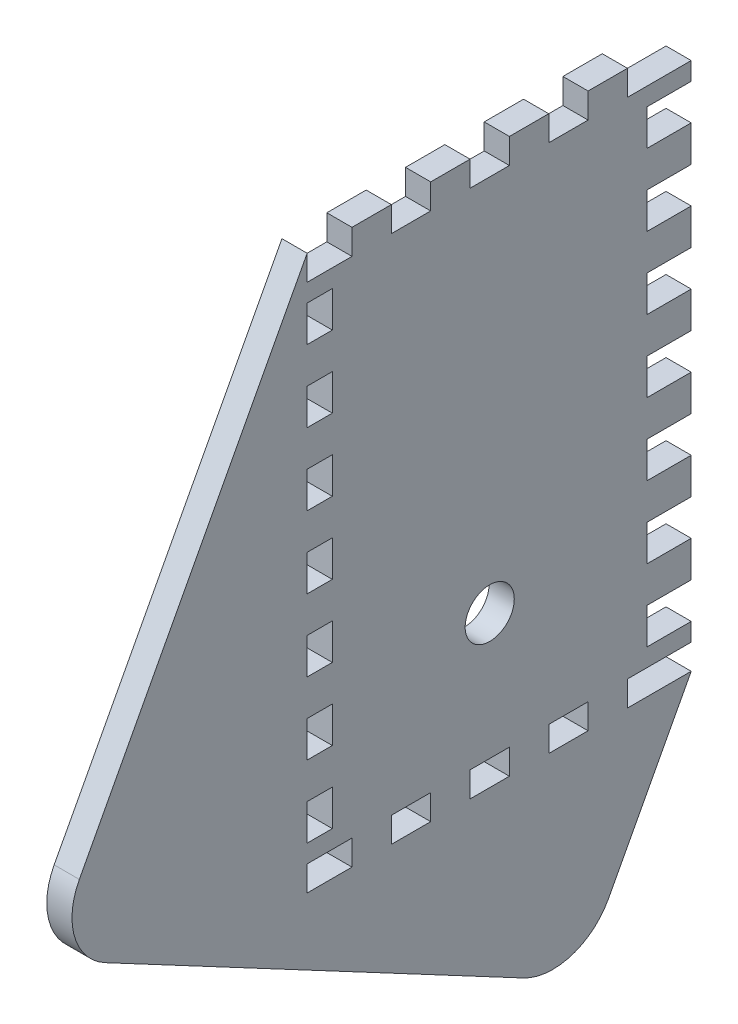
SolidWorks part; units mm, degrees
ref_plane "Piano frontale" through (0, 0, 0) normal (0, 0, 1) x (1, 0, 0)
ref_plane "Piano superiore" through (0, 0, 0) normal (0, 1, 0) x (1, 0, 0)
ref_plane "Piano destro" through (0, 0, 0) normal (1, 0, 0) x (0, 0, -1)
sketch "Schizzo1" plane through (0, 0, 0) normal (1, 0, 0) x (0, 0, -1)
  line L1 (0, 0) -> (50, 0)
  line L2 (0, 0) -> (0, 80)
  line L3 (0, 80) -> (50, 80)
  line L4 (50, 0) -> (50, 80)
  dimension "D1" = 80
  dimension "D2" = 50
extrude "Estrusione-Estrusione1" add sketch "Schizzo1" along normal blind 4
sketch "Schizzo2" plane through (4, 0, 0) normal (1, 0, 0) x (0, 0, -1)
  line L0 (0, 80) -> (0, 0) construction
  line L1 (0, 77.1429) -> (-4, 77.1429)
  line L2 (0, 77.1429) -> (0, 80)
  line L3 (0, 80) -> (-4, 80)
  line L4 (-4, 77.1429) -> (-4, 80)
  line L6 (50, 80) -> (57, 80)
  line L7 (50, 80) -> (50, 77.1429)
  line L8 (50, 77.1429) -> (57, 77.1429)
  line L9 (57, 80) -> (57, 77.1429)
  line L10 (50, 0) -> (57, 0)
  line L11 (50, 0) -> (50, 2.8571)
  line L12 (50, 2.8571) -> (57, 2.8571)
  line L13 (57, 0) -> (57, 2.8571)
  line L14 (0, 0) -> (-4, 0)
  line L15 (0, 0) -> (0, 2.8571)
  line L16 (0, 2.8571) -> (-4, 2.8571)
  line L17 (-4, 0) -> (-4, 2.8571)
  dimension "D1" = 4
  dimension "D2" = 7
  dimension "D3" = 2.8571
  dimension "D4" = 2.8571
extrude "Estrusione-Estrusione2" add sketch "Schizzo2" against normal blind 4
sketch "Schizzo3" plane through (4, 0, 0) normal (1, 0, 0) x (0, 0, -1)
  line L0 (0, 77.1429) -> (0, 2.8571) construction
  line L1 (0, 71.4286) -> (-4, 71.4286)
  line L2 (0, 71.4286) -> (0, 65.7143)
  line L3 (0, 65.7143) -> (-4, 65.7143)
  line L4 (-4, 71.4286) -> (-4, 65.7143)
  line L5 (50, 2.8571) -> (50, 77.1429) construction
  line L6 (50, 71.4286) -> (57, 71.4286)
  line L7 (50, 71.4286) -> (50, 65.7143)
  line L8 (50, 65.7143) -> (57, 65.7143)
  line L9 (57, 71.4286) -> (57, 65.7143)
  line L10 (-4, 77.1429) -> (0, 77.1429) construction
  line L11 (-4, 80) -> (-4, 77.1429) construction
  line L12 (57, 77.1429) -> (57, 80) construction
  dimension "D1" = 5.7143
  dimension "D2" = 5.7143
extrude "Estrusione-Estrusione3" add sketch "Schizzo3" against normal blind 4
pattern_linear "Ripetizione a L1" count 6 spacing 11.4286 along (0, -1, 0) of "Estrusione-Estrusione3"
sketch "Schizzo4" plane through (4, 0, 0) normal (1, 0, 0) x (0, 0, -1)
  line L0 (57, 80) -> (-4, 80) construction
  line L1 (3.125, 80) -> (9.375, 80)
  line L2 (3.125, 80) -> (3.125, 84)
  line L3 (3.125, 84) -> (9.375, 84)
  line L4 (9.375, 80) -> (9.375, 84)
  line L5 (-4, 0) -> (57, 0) construction
  line L6 (3.125, 0) -> (9.375, 0)
  line L7 (3.125, 0) -> (3.125, -4)
  line L8 (3.125, -4) -> (9.375, -4)
  line L9 (9.375, 0) -> (9.375, -4)
  line L10 (0, 77.1429) -> (0, 71.4286) construction
  point P14 (6.25, 0)
  dimension "D1" = 3.125
  dimension "D2" = 6.25
  dimension "D3" = 4
  dimension "D4" = 4
extrude "Estrusione-Estrusione4" add sketch "Schizzo4" against normal blind 4
pattern_linear "Ripetizione a L2" count 4 spacing 12.5 along (0, 0, -1) of "Estrusione-Estrusione4"
sketch "Schizzo5" plane through (4, 0, 0) normal (1, 0, 0) x (0, 0, -1)
  line L0 (46.875, -4) -> (57, -4)
  line L1 (57, -4) -> (39.1601, -37.552)
  line L2 (39.1601, -37.552) -> (-44.873, 7.1291)
  line L3 (-44.873, 7.1291) -> (-4, 84)
  line L4 (-4, 84) -> (-4, 80)
  line L5 (-4, 80) -> (-4, 77.1429) construction
  line L6 (3.125, 80) -> (-4, 80) construction
  line L7 (-4, 80) -> (-4, -4)
  line L8 (-4, -4) -> (46.875, -4)
  dimension "D1" = 4
  dimension "D2" = 10.125
  dimension "D3" = 62
  dimension "D4" = 38
extrude "Estrusione-Estrusione5" add sketch "Schizzo5" against normal blind 4
fillet "Raccordo1" radius 10 2 edges at (2, -37.552, -39.1601) (2, 7.1291, 44.873)
sketch "Schizzo6" plane through (4, 0, 0) normal (1, 0, 0) x (0, 0, -1)
  line L0 (21.875, 0) -> (28.125, 0) construction
  line L1 (0, 20) -> (0, 14.2857) construction
  circle A0 centre (25, 20) radius 3.9
  dimension "D1" = 7.8
  dimension "D2" = 20
  dimension "D3" = 25
extrude "Taglio-Estrusione1" cut sketch "Schizzo6" against normal blind 4
equation "\"WFront\"= 140mm"
equation "\"HFront\"= 80mm"
equation "\"DFront\"= 4mm"
equation "\"WLeft\"= 50mm"
equation "\"HLeft\"= 80mm"
equation "\"DLeft\"= 4mm"
equation "\"WTop\"= 140mm"
equation "\"HTop\"= 50mm"
equation "\"DTop\"= 4mm"
equation "\"N_Denti_W\"= 10"
equation "\"N_Denti_H\"= 7"
equation "\"N_Denti_D\"= 4"
equation "\"HDistDenti\"= \"HFront\" / \"N_Denti_H\""
equation "\"WDistDenti\"= \"WFront\" / \"N_Denti_W\""
equation "\"DDistDenti\"= \"WLeft\" / \"N_Denti_D\""
equation "\"HDenti\"= \"HDistDenti\" / 2"
equation "\"WDenti\"= \"WDistDenti\" / 2"
equation "\"DDenti\"= \"DDistDenti\" / 2"
equation "\"WDisplay\"= 95mm"
equation "\"HDisplay\"= 61mm"
equation "\"CEnc\"= 7mm"
equation "\"Display_to_Enc_W\"= 11.5 + \"CEnc\" / 2"
equation "\"Display_to_Dx\"= 32mm"
equation "\"Display_to_Top\"= 10mm"
equation "\"Display_to_Enc_H\"= 24 + \"CEnc\" / 2"
equation "\"D1@Schizzo1\"=\"HLeft\""
equation "\"D2@Schizzo1\"=\"WLeft\""
equation "\"D1@Estrusione-Estrusione1\"=\"DLeft\""
equation "\"D1@Schizzo2\"=\"DFront\""
equation "\"D2@Schizzo2\"=\"DFront\"+\"DMask\""
equation "\"D3@Schizzo2\"=\"HDenti\"/2"
equation "\"D4@Schizzo2\"=\"HDenti\"/2 "
equation "\"D1@Estrusione-Estrusione2\"=\"DLeft\""
equation "\"D1@Schizzo3\"=\"HDenti\""
equation "\"D2@Schizzo3\"=\"HDenti\""
equation "\"D1@Estrusione-Estrusione3\"=\"DLeft\""
equation "\"D1@Ripetizione a L1\"=\"N_Denti_H\"-1"
equation "\"D1@Schizzo4\"=\"DDenti\"/2"
equation "\"D2@Schizzo4\"=\"DDenti\""
equation "\"D3@Schizzo4\"=\"DTop\""
equation "\"D4@Schizzo4\"=\"DTop\""
equation "\"D1@Estrusione-Estrusione4\"=\"DLeft\""
equation "\"D3@Ripetizione a L2\"=\"DDistDenti\""
equation "\"D1@Ripetizione a L2\"=\"N_Denti_D\""
equation "\"D1@Schizzo5\"=\"DTop\""
equation "\"D2@Schizzo5\"=\"DFront\"+\"DDenti\"/2 + \"DMask\""
equation "\"D1@Estrusione-Estrusione5\"=\"DLeft\""
equation "\"DMask\"= 3mm"
equation "\"D3@Schizzo6\"=\"WLeft\"/2"
equation "\"D1@Taglio-Estrusione1\"=\"DLeft\""
